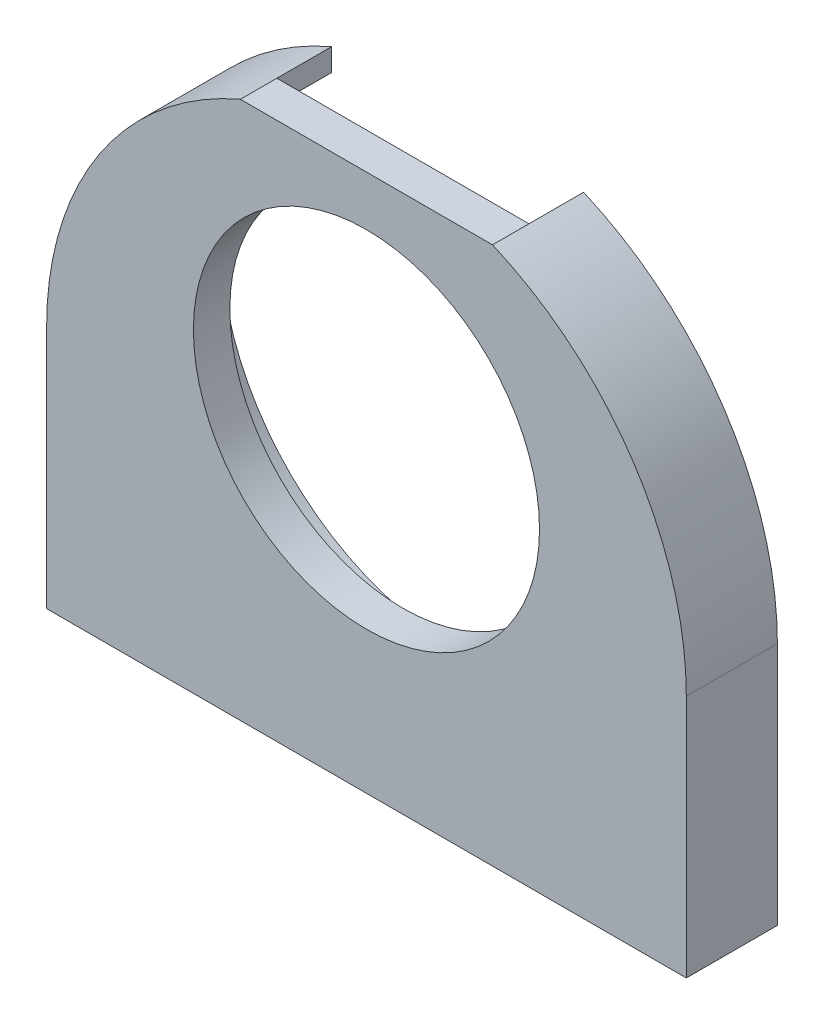
SolidWorks part; units mm, degrees
ref_plane "Front Plane" through (0, 0, 0) normal (0, 0, 1) x (1, 0, 0)
ref_plane "Top Plane" through (0, 0, 0) normal (0, 1, 0) x (1, 0, 0)
ref_plane "Right Plane" through (0, 0, 0) normal (1, 0, 0) x (0, 0, -1)
sketch "Sketch1" plane through (0, 0, 0) normal (0, 0, 1) x (1, 0, 0)
  line L0 (5.32, 14.0026) -> (5.32, 14.6195)
  line L1 (0, 0) -> (17.56, 0)
  line L2 (0, 0) -> (0, 6.55)
  line L3 (0, 6.55) -> (17.56, 6.55)
  line L4 (17.56, 0) -> (17.56, 6.55)
  line L6 (12.24, 14.0026) -> (12.24, 14.6195)
  arc A0 (5.32, 14.6195) -> (0, 6.55) centre (8.78, 6.55) ccw
  arc A1 (5.32, 14.0026) -> (12.24, 14.0026) centre (8.78, 8.5) ccw
  arc A2 (17.56, 6.55) -> (12.24, 14.6195) centre (8.78, 6.55) ccw
  dimension "D4" = 13
  dimension "D1" = 17.56
  dimension "D2" = 6.55
  dimension "D5" = 1.95
  dimension "D6" = 5.32
extrude "Boss-Extrude1" add sketch "Sketch1" along normal blind 1.5 contours A1 L3 L2 L1 L4 | A1 L0 A0 L3 | L3 A2 L6 A1
sketch "Sketch3" plane through (0, 0, 1.5) normal (0, 0, 1) x (1, 0, 0)
  line L5 (5.32, 14.0026) -> (5.32, 14.6195)
  line L6 (0, 6.55) -> (0, 0)
  line L7 (0, 0) -> (17.56, 0)
  line L8 (17.56, 0) -> (17.56, 6.55)
  line L9 (12.24, 14.6195) -> (12.24, 14.0026)
  line L10 (5.32, 14.0026) -> (5.32, 14.6195)
  line L11 (0, 6.55) -> (0, 0)
  line L12 (0, 0) -> (17.56, 0)
  line L13 (17.56, 0) -> (17.56, 6.55)
  line L14 (12.24, 14.6195) -> (12.24, 14.0026)
  line L15 (0, 0) -> (17.56, 0)
  line L16 (17.56, 6.55) -> (17.56, 0)
  line L17 (0, 0) -> (0, 6.55)
  line L18 (5.32, 14.6195) -> (12.24, 14.6195)
  arc A3 (5.32, 14.0026) -> (12.24, 14.0026) centre (8.78, 8.5) ccw
  arc A4 (5.32, 14.6195) -> (0, 6.55) centre (8.78, 6.55) ccw
  arc A5 (17.56, 6.55) -> (12.24, 14.6195) centre (8.78, 6.55) ccw
  arc A6 (5.32, 14.0026) -> (12.24, 14.0026) centre (8.78, 8.5) ccw
  arc A7 (5.32, 14.6195) -> (0, 6.55) centre (8.78, 6.55) ccw
  arc A8 (17.56, 6.55) -> (12.24, 14.6195) centre (8.78, 6.55) ccw
  arc A9 (17.56, 6.55) -> (12.24, 14.6195) centre (8.78, 6.55) ccw
  arc A10 (0, 6.55) -> (5.32, 14.6195) centre (8.78, 6.55) cw
  arc M9 (12.24, 14.0026) -> (5.32, 14.0026) centre (8.78, 8.5) cw
  line M10 (5.32, 14.0026) -> (5.32, 14.6195)
  arc M11 (5.32, 14.6195) -> (0, 6.55) centre (8.78, 6.55) ccw
  line M12 (0, 6.55) -> (0, 0)
  line M13 (0, 0) -> (17.56, 0)
  line M14 (17.56, 0) -> (17.56, 6.55)
  arc M15 (17.56, 6.55) -> (12.24, 14.6195) centre (8.78, 6.55) ccw
  line M16 (12.24, 14.6195) -> (12.24, 14.0026)
  dimension "D1" = 0
extrude "Boss-Extrude2" add sketch "Sketch3" along normal blind 1 contours M16 M9 M10 M11 M12 M13 M14 M15 | L18 M10 M9 M16
sketch "Sketch4" plane through (0, 0, 1.5) normal (0, 0, -1) x (-1, 0, 0)
  circle A0 centre (-8.78, 8.5) radius 4.75
  dimension "D1" = 9.5
extrude "Cut-Extrude1" cut sketch "Sketch4" against normal through all
sketch "Sketch5" plane through (0, 0, 0) normal (0, -1, 0) x (1, 0, 0)
  line L1 (0, 2.5) -> (17.56, 2.5)
  line L2 (0, 2.5) -> (0, 0)
  line L3 (0, 0) -> (17.56, 0)
  line L4 (17.56, 2.5) -> (17.56, 0)
extrude "Boss-Extrude3" add sketch "Sketch5" along normal blind 0.15
